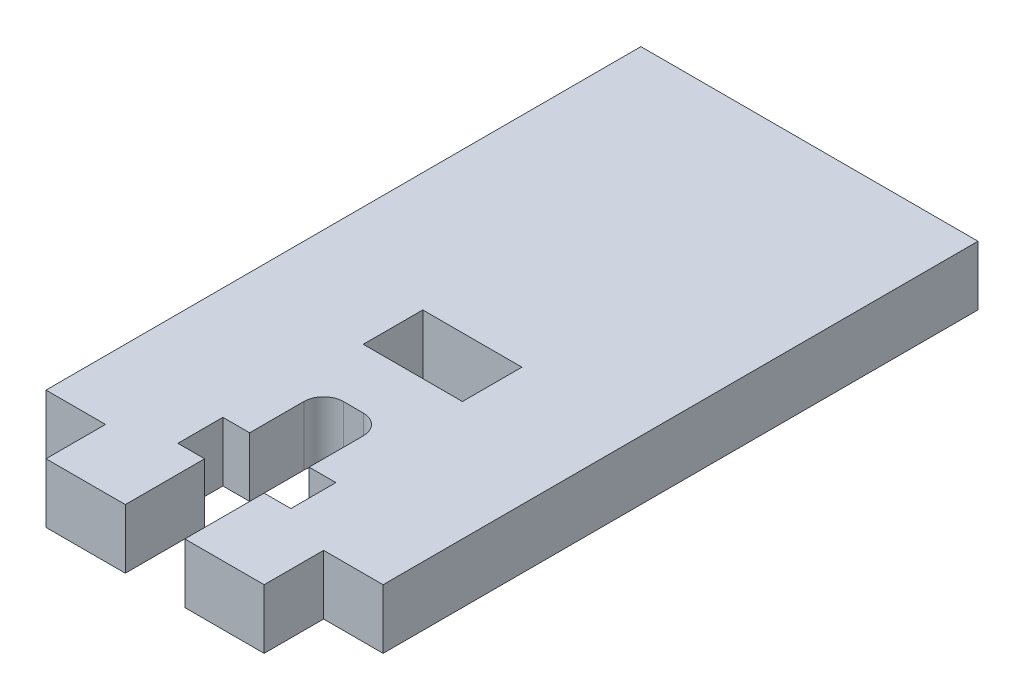
SolidWorks part; units mm, degrees
ref_plane "Plano frontal" through (0, 0, 0) normal (0, 0, 1) x (1, 0, 0)
ref_plane "Plano superior" through (0, 0, 0) normal (0, 1, 0) x (1, 0, 0)
ref_plane "Plano direito" through (0, 0, 0) normal (1, 0, 0) x (0, 0, -1)
sketch "Sketch1" plane through (0, 0, 0) normal (0, 1, 0) x (1, 0, 0)
  line L1 (-8.5, 15) -> (8.5, 15)
  line L2 (-8.5, 15) -> (-8.5, -15)
  line L3 (-8.5, -15) -> (8.5, -15)
  line L4 (8.5, 15) -> (8.5, -15)
  point P4 (0, 15)
  point P6 (-8.5, 0)
  dimension "D1" = 30
  dimension "D2" = 17
extrude "Boss-Extrude1" add sketch "Sketch1" along normal mid plane 3
sketch "Sketch2" plane through (0, 0, 0) normal (0, 1, 0) x (1, 0, 0)
  line L0 (-8.5, -15) -> (8.5, -15) construction
  line L1 (-5.5, -15) -> (5.5, -15)
  line L2 (-5.5, -15) -> (-5.5, -18)
  line L3 (-5.5, -18) -> (5.5, -18)
  line L4 (5.5, -15) -> (5.5, -18)
  line L8 (8.5, -15) -> (8.5, 15) construction
  point P6 (0, -15)
  dimension "D1" = 3
  dimension "D3" = 11
  dimension "D4" = 3
extrude "Boss-Extrude2" add sketch "Sketch2" along normal mid plane 3
sketch "Sketch4" plane through (0, 0, 0) normal (0, 1, 0) x (1, 0, 0)
  line L0 (-5.5, -18) -> (5.5, -18) construction
  line L1 (-1.5, -18) -> (1.5, -18)
  line L2 (-1.5, -18) -> (-1.5, -14)
  line L3 (-0.5, -8) -> (0.5, -8)
  line L4 (1.5, -18) -> (1.5, -14)
  line L5 (-5.5, -15) -> (-5.5, -18) construction
  line L7 (1.5, -11.73) -> (2.85, -11.73)
  line L8 (-2.85, -11.73) -> (-1.5, -11.73)
  line L9 (-2.85, -11.73) -> (-2.85, -14)
  line L10 (-2.85, -14) -> (-1.5, -14)
  line L11 (2.85, -11.73) -> (2.85, -14)
  line L12 (-1.5, -11.73) -> (-1.5, -9)
  line L13 (1.5, -14) -> (2.85, -14)
  line L14 (1.5, -11.73) -> (1.5, -9)
  arc A0 (0.5, -8) -> (1.5, -9) centre (0.5, -9) cw
  arc A1 (-1.5, -9) -> (-0.5, -8) centre (-0.5, -9) cw
  point P18 (1.5, -8)
  point P21 (-1.5, -8)
  dimension "D8" = 1
  dimension "D1" = 3
  dimension "D2" = 4
  dimension "D3" = 10
  dimension "D4" = 1.35
  dimension "D5" = 1.35
  dimension "D6" = 2.27
  dimension "D7" = 4
sketch "Sketch3" plane through (0, 0, 0) normal (0, 1, 0) x (1, 0, 0)
  line L1 (-2.5, -2) -> (2.5, -2)
  line L2 (-2.5, -2) -> (-2.5, -5)
  line L3 (-2.5, -5) -> (2.5, -5)
  line L4 (2.5, -2) -> (2.5, -5)
  line L5 (-8.5, -15) -> (-5.5, -15) construction
  point P6 (0, -2)
  dimension "D1" = 3
  dimension "D2" = 10
  dimension "D3" = 5
extrude "Cut-Extrude1" cut sketch "Sketch3" against normal through all both and the other way through all
extrude "Cut-Extrude2" cut sketch "Sketch4" against normal through all both and the other way through all
